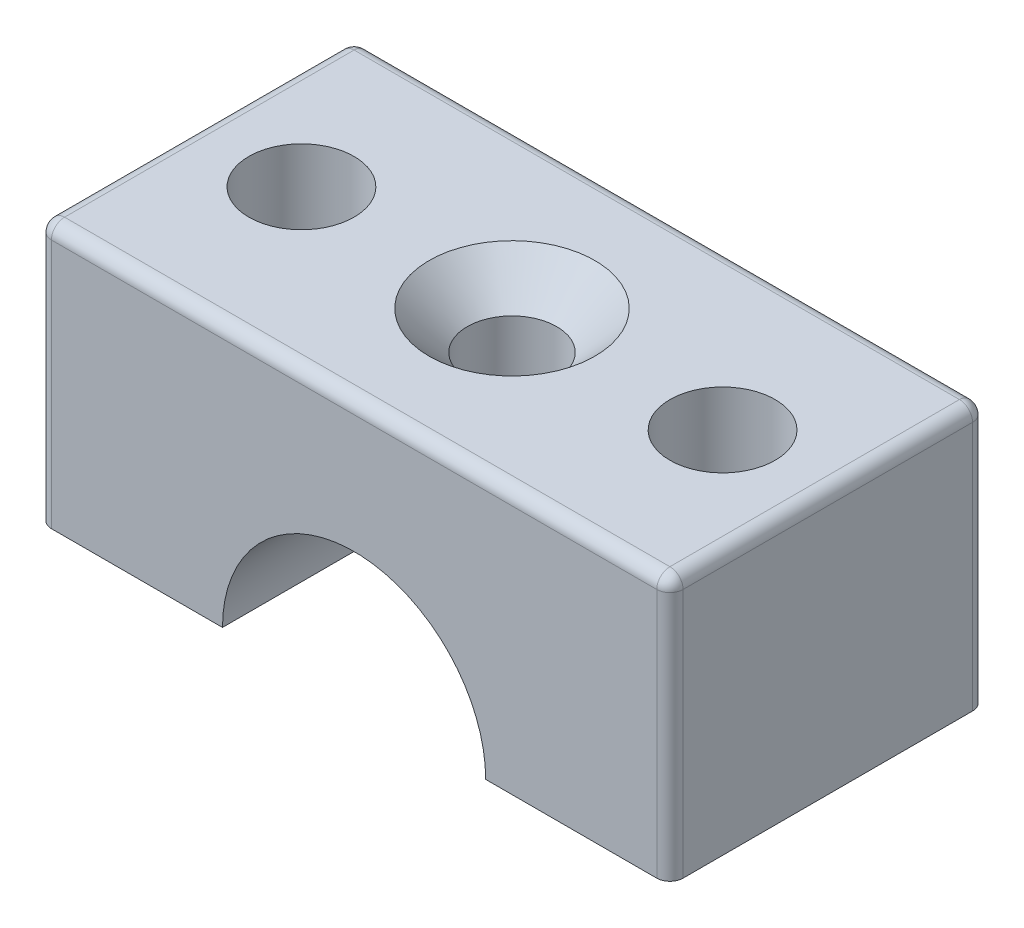
SolidWorks part; units mm, degrees
ref_plane "Front Plane" through (0, 0, 0) normal (0, 0, 1) x (1, 0, 0)
ref_plane "Top Plane" through (0, 0, 0) normal (0, 1, 0) x (1, 0, 0)
ref_plane "Right Plane" through (0, 0, 0) normal (1, 0, 0) x (0, 0, -1)
sketch "Sketch1" plane through (0, 0, 0) normal (0, 0, 1) x (1, 0, 0)
  line L0 (17, 0) -> (24, 0)
  line L1 (0, 0) -> (7, 0)
  line L2 (0, 0) -> (0, 10)
  line L3 (0, 10) -> (24, 10)
  line L4 (24, 0) -> (24, 10)
  arc A0 (17, 0) -> (7, 0) centre (12, 0) ccw
  dimension "D2" = 10
  dimension "D1" = 10
  dimension "D3" = 24
  dimension "D4" = 12
extrude "Boss-Extrude1" add sketch "Sketch1" along normal blind 12
sketch "Sketch2" plane through (0, 10, 0) normal (0, 1, 0) x (1, 0, 0)
  line L0 (12, 0) -> (12, -12) construction
  line L1 (24, 0) -> (0, 0) construction
  line L2 (24, -12) -> (0, -12) construction
  circle A0 centre (4, -6) radius 2
  circle A1 centre (20, -6) radius 2
  point P4 (0, 0)
  point P11 (0, 0)
  dimension "D3" = 4
  dimension "D1" = 8
  dimension "D2" = 6
extrude "Cut-Extrude1" cut sketch "Sketch2" against normal through all
hole_wizard "CSK for M3 Flat Head Machine Screw1" positions "Sketch4" profile "Sketch5" countersink size "M3" standard "ANSI Metric" end condition through all
sketch "Sketch4" plane through (0, 10, 0) normal (0, 1, 0) x (1, 0, 0)
  line L0 (24, 0) -> (0, 0) construction
  line L1 (0, -12) -> (0, 0) construction
  point P0 (12, -6)
  dimension "D1" = 6
  dimension "D2" = 12
sketch "Sketch5" plane through (12, 10, 6) normal (1, 0, 0) x (0, 0, 1)
  line L0 (0, 0) -> (0, 10)
  line L1 (0, 10) -> (1.7, 10)
  line L2 (1.7, 10) -> (1.7, 1.45)
  line L3 (1.7, 1.45) -> (3.15, 0)
  line L5 (3.15, 0) -> (0, 0)
  line L6 (-1.7, 1.45) -> (-3.15, 0) construction
  line L11 (0, -6.35) -> (0, 107.95) construction
  dimension "Thru Hole Dia." = 3.4
  dimension "Thru Hole Depth" = 10
  dimension "Near C'Sink Dia." = 6.3
  dimension "Near C'Sink Angle" = 90
fillet "Fillet1" radius 0.5 8 edges at (0, 5, 0) (12, 10, 0) (0, 10, 6) (24, 5, 0) (24, 5, 12) (0, 5, 12) (24, 10, 6) (12, 10, 12)
